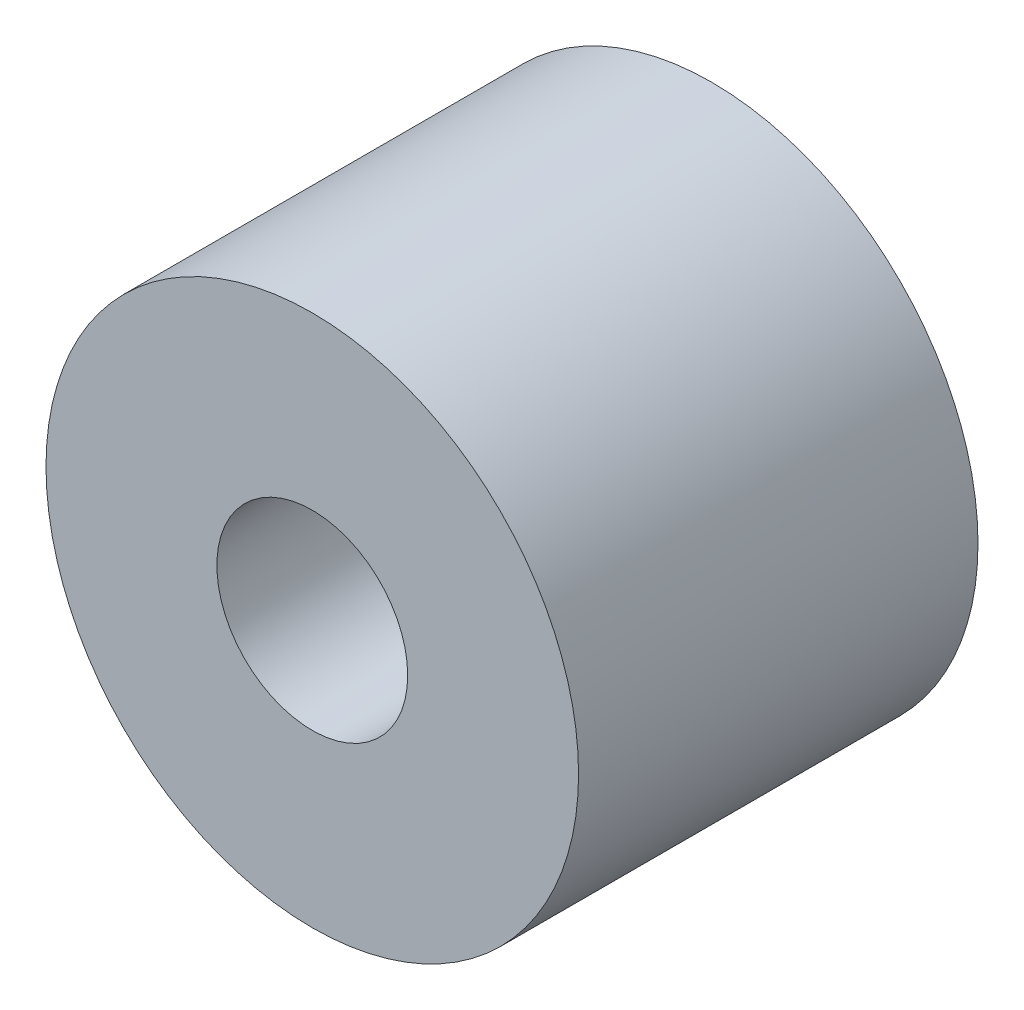
SolidWorks part; units mm, degrees
ref_plane "前视基准面" through (0, 0, 0) normal (0, 0, 1) x (1, 0, 0)
ref_plane "上视基准面" through (0, 0, 0) normal (0, 1, 0) x (1, 0, 0)
ref_plane "右视基准面" through (0, 0, 0) normal (1, 0, 0) x (0, 0, -1)
other "Configuration Table"
sketch "草图1" plane through (0, 0, 0) normal (0, 0, 1) x (1, 0, 0)
  circle A0 centre (0, 0) radius 6
  circle A1 centre (0, 0) radius 2.15
  dimension "D1" = 12
  dimension "D2" = 4.3
extrude "凸台-拉伸1" add sketch "草图1" along normal blind 9
